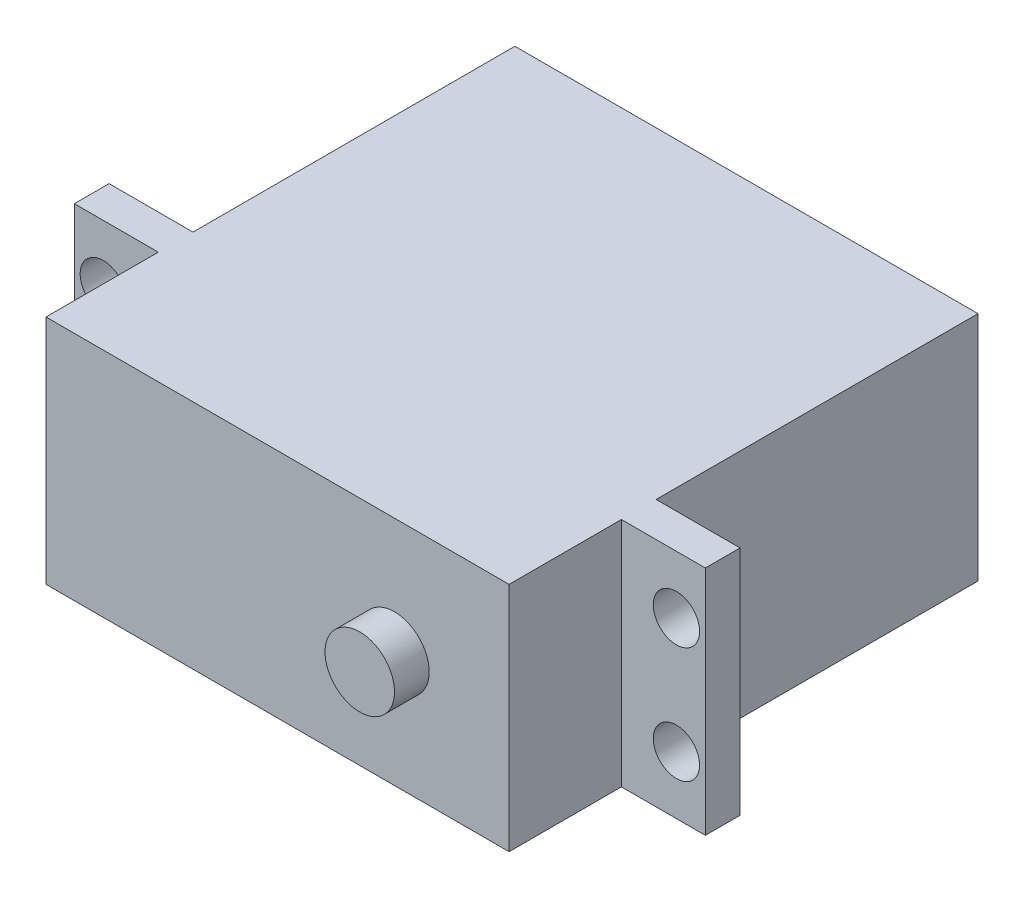
SolidWorks part; units mm, degrees
ref_plane "前视基准面" through (0, 0, 0) normal (0, 0, 1) x (1, 0, 0)
ref_plane "上视基准面" through (0, 0, 0) normal (0, 1, 0) x (1, 0, 0)
ref_plane "右视基准面" through (0, 0, 0) normal (1, 0, 0) x (0, 0, -1)
sketch "草图1" plane through (0, 0, 0) normal (0, 0, 1) x (1, 0, 0)
  line L1 (-20, 10) -> (20, 10)
  line L2 (-20, 10) -> (-20, -10)
  line L3 (-20, -10) -> (20, -10)
  line L4 (20, 10) -> (20, -10)
  line L5 (0, -10) -> (0, 10) construction
  line L6 (-20, 0) -> (20, 0) construction
  point P0 (0, 0)
  dimension "D1" = 20
  dimension "D2" = 40
extrude "凸台-拉伸1" add sketch "草图1" along normal blind 40.5
ref_plane "基准面1" through (0, 0, 27.8) normal (0, 0, -1) x (-1, 0, 0)
sketch "草图2" plane through (0, 0, 27.8) normal (0, 0, -1) x (-1, 0, 0)
  line L0 (-20, 10) -> (-27.25, 10)
  line L1 (-20, -10) -> (-20, 10) construction
  line L2 (-27.25, 10) -> (-27.25, -10)
  line L3 (-27.25, -10) -> (-20, -10)
  line L4 (-20, 10) -> (-20, -10)
  line L5 (0, 0) -> (0, 7.3474) construction
  line L6 (20, 10) -> (20, -10)
  line L7 (27.25, -10) -> (20, -10)
  line L8 (27.25, 10) -> (27.25, -10)
  line L9 (20, 10) -> (27.25, 10)
  point P4 (-27.25, 0)
  dimension "D1" = 27.25
extrude "凸台-拉伸2" add sketch "草图2" against normal blind 3
sketch "草图3" plane through (0, 0, 30.8) normal (0, 0, 1) x (1, 0, 0)
  line L0 (0, 0) -> (0, -5.1325) construction
  circle A0 centre (-24.75, 5) radius 2
  circle A1 centre (-24.75, -5) radius 2
  circle A2 centre (24.75, -5) radius 2
  circle A3 centre (24.75, 5) radius 2
  dimension "D1" = 4
  dimension "D2" = 4
  dimension "D4" = 5
  dimension "D3" = 10
  dimension "D5" = 24.75
extrude "切除-拉伸1" cut sketch "草图3" against normal blind 5
sketch "草图4" plane through (0, 0, 40.5) normal (0, 0, 1) x (1, 0, 0)
  line L0 (20, -10) -> (20, 10) construction
  circle A0 centre (10.1, 0) radius 3
  point P4 (0, 0)
  dimension "D2" = 6
  dimension "D1" = 9.9
extrude "凸台-拉伸3" add sketch "草图4" along normal blind 3
ref_plane "基准面2" through (0, 0, 47.5) normal (0, 0, -1) x (-1, 0, 0)
